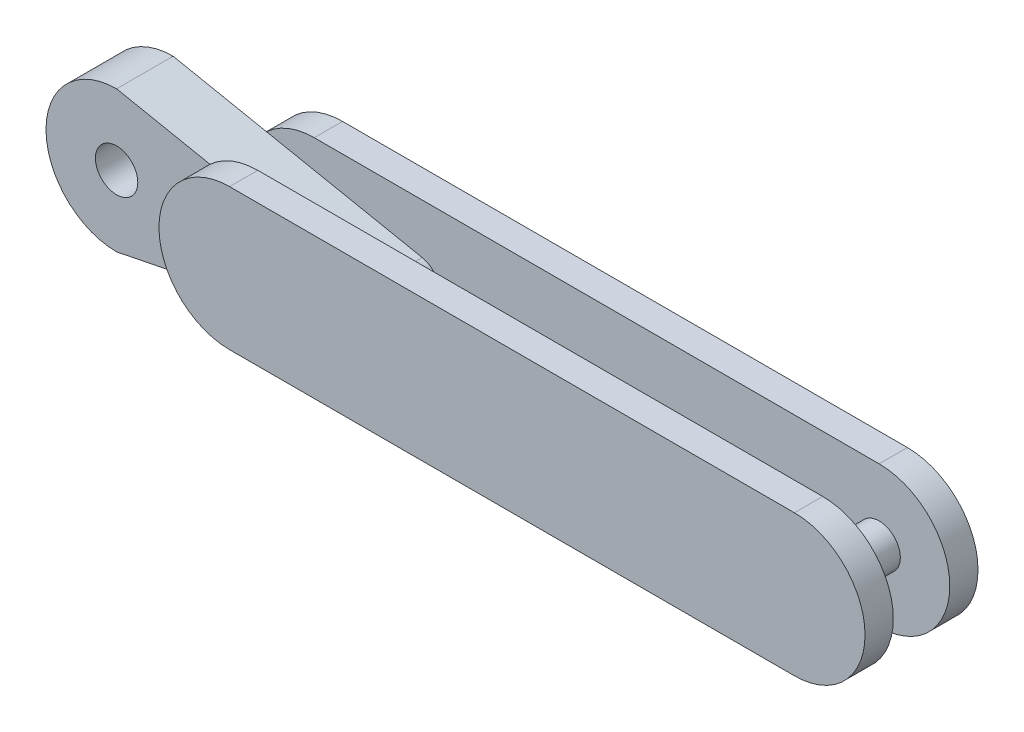
SolidWorks part; units mm, degrees
material "1060 Alloy"
ref_plane "Front Plane" through (0, 0, 0) normal (0, 0, 1) x (1, 0, 0)
ref_plane "Top Plane" through (0, 0, 0) normal (0, 1, 0) x (1, 0, 0)
ref_plane "Right Plane" through (0, 0, 0) normal (1, 0, 0) x (0, 0, -1)
sketch "Sketch4" plane through (0, 0, 0) normal (0, 0, 1) x (1, 0, 0)
  line L0 (-250, 0) -> (250, 0) construction
  line L1 (-250, 50) -> (250, 50)
  line L2 (-250, -50) -> (250, -50)
  arc A0 (-250, 50) -> (-250, -50) centre (-250, 0) ccw
  arc A1 (250, -50) -> (250, 50) centre (250, 0) ccw
  point P3 (0, 0)
  dimension "D2" = 50
  dimension "D1" = 500
extrude "Boss-Extrude2" add sketch "Sketch4" along normal mid plane 80
sketch "Sketch5" plane through (0, 0, 40) normal (0, 0, 1) x (1, 0, 0)
  line L0 (-150, 50) -> (-250, 50)
  line L1 (-250, -50) -> (-150, -50)
  arc A0 (-250, 50) -> (-250, -50) centre (-250, 0) ccw
  arc A2 (-150, 50) -> (-150, -50) centre (-150, 0) ccw
extrude "Cut-Extrude2" cut sketch "Sketch5" against normal blind 20
sketch "Sketch6" plane through (0, 0, -40) normal (0, 0, -1) x (-1, 0, 0)
  line L0 (150, 50) -> (250, 50)
  line L1 (150, -50) -> (250, -50)
  arc A0 (250, -50) -> (250, 50) centre (250, 0) ccw
  arc A2 (150, -50) -> (150, 50) centre (150, 0) ccw
extrude "Cut-Extrude3" cut sketch "Sketch6" against normal blind 20
sketch "Sketch9" plane through (0, 0, 20) normal (0, 0, 1) x (1, 0, 0)
  circle A0 centre (-250, 0) radius 15
extrude "Cut-Extrude5" cut sketch "Sketch9" against normal blind 40
ref_plane "Plane1" through (0, 0, 0) normal (0, 0, 1) x (1, 0, 0)
sketch "Sketch10" plane through (0, 0, 0) normal (0, 0, 1) x (1, 0, 0)
  line L12 (-250, 50) -> (-73.5436, 14.7087)
  line L14 (-250, 50) -> (250, 50)
  line L15 (250, -50) -> (-250, -50)
  line L17 (-73.5436, -14.7087) -> (-250, -50)
  arc A7 (250, -50) -> (250, 50) centre (250, 0) ccw
  arc A8 (-73.5436, -14.7087) -> (-73.5436, 14.7087) centre (-76.4853, 0) ccw
extrude "Cut-Extrude6" cut sketch "Sketch10" against normal mid plane 40
sketch "Sketch11" plane through (0, 0, 40) normal (0, 0, 1) x (1, 0, 0)
  circle A0 centre (250, 0) radius 15
sketch "Sketch13" plane through (0, 0, 40) normal (0, 0, 1) x (1, 0, 0)
  circle A0 centre (250, 0) radius 15
extrude "Boss-Extrude4" add sketch "Sketch13" against normal up to surface (60 mm away) up to face at (-31.9088, 0, -20)
extrude "Boss-Extrude3" add sketch "Sketch11" against normal blind 80
sketch "Sketch12" plane through (0, 0, 0) normal (0, 0, 1) x (1, 0, 0)
  point P0 (-250, 0)
move or copy body "Body-Move/Copy1" bodies to move or copy 110 copy no translate (250, 0, 0)
